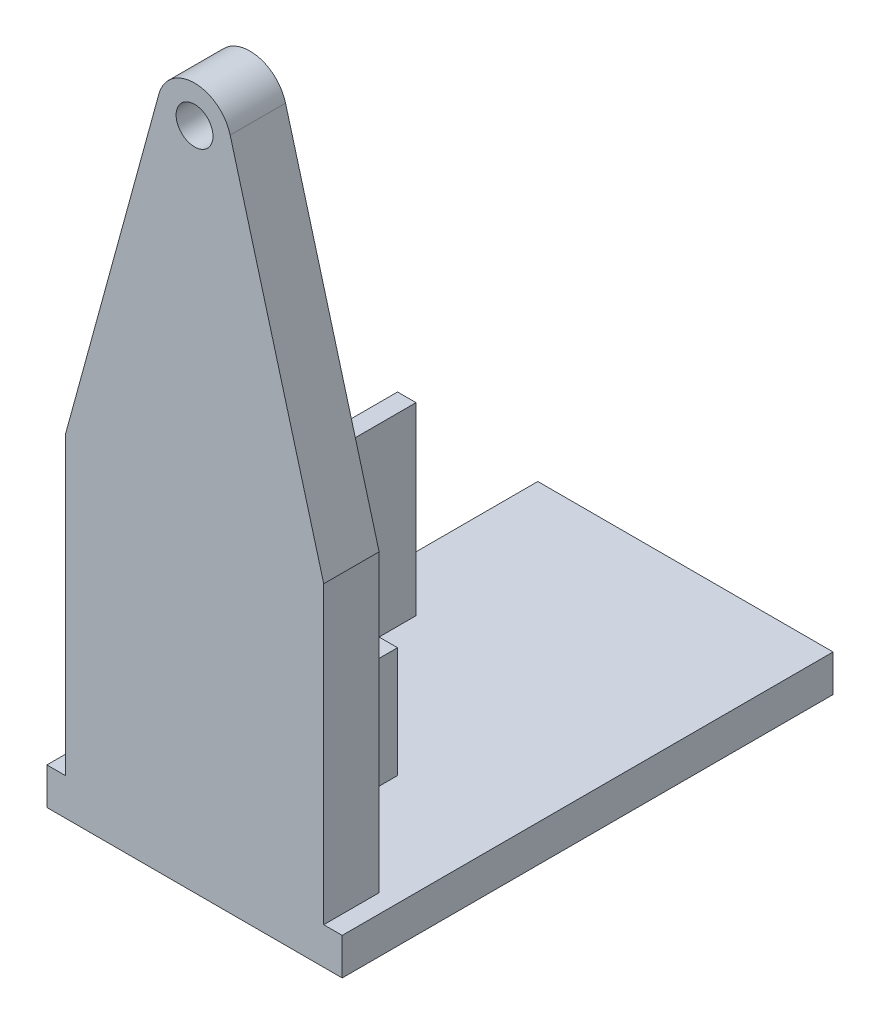
SolidWorks part; units mm, degrees
ref_plane "Front Plane" through (0, 0, 0) normal (0, 0, 1) x (1, 0, 0)
ref_plane "Top Plane" through (0, 0, 0) normal (0, 1, 0) x (1, 0, 0)
ref_plane "Right Plane" through (0, 0, 0) normal (1, 0, 0) x (0, 0, -1)
sketch "Sketch1" plane through (0, 0, 0) normal (0, 0, 1) x (1, 0, 0)
  line L0 (-40, 0) -> (40, 0)
  line L1 (40, 0) -> (40, 10)
  line L2 (40, 10) -> (-40, 10)
  line L3 (35, 10) -> (35, 90)
  line L4 (35, 90) -> (9.6562, 182.5997)
  line L5 (0, 0) -> (0, 190) construction
  line L6 (-35, 90) -> (-9.6453, 182.6398)
  line L7 (-35, 10) -> (-35, 90)
  line L8 (-40, 0) -> (-40, 10)
  circle A0 centre (0, 180) radius 10
  circle A1 centre (0, 180) radius 5
  point P4 (0, 180)
  point P12 (0, 10)
  dimension "D1" = 20
  dimension "D7" = 10
  dimension "D2" = 40
  dimension "D3" = 10
  dimension "D4" = 35
  dimension "D5" = 80
  dimension "D6" = 170
extrude "Boss-Extrude1" add sketch "Sketch1" along normal blind 15 contours L5 L0 L1 L2 | L2 L5 L6 L7 | L5 L2 L3 L4 | A0 | A1
sketch "Sketch2" plane through (0, 0, 0) normal (0, 0, -1) x (-1, 0, 0)
  line L1 (-40, 0) -> (40, 0)
  line L2 (-40, 0) -> (-40, 10)
  line L3 (-40, 10) -> (40, 10)
  line L4 (40, 0) -> (40, 10)
extrude "Boss-Extrude2" add sketch "Sketch2" along normal blind 118
sketch "Sketch3" plane through (0, 0, 0) normal (0, 0, -1) x (-1, 0, 0)
  line L0 (-10, 10) -> (10, 10)
  line L1 (35, 10) -> (-35, 10) construction
  line L2 (10, 10) -> (10, 40)
  line L3 (0, 180) -> (0, 10) construction
  line L4 (10, 40) -> (-10, 40)
  line L5 (-10, 10) -> (-10, 40)
  line L6 (-10, 100) -> (-15, 100)
  line L7 (10, 50) -> (15, 50)
  line L8 (10, 50) -> (10, 100)
  line L9 (10, 100) -> (15, 100)
  line L10 (15, 50) -> (15, 100)
  line L11 (-10, 50) -> (-10, 100)
  line L12 (-10, 50) -> (-15, 50)
  line L13 (-15, 50) -> (-15, 100)
  dimension "D1" = 10
  dimension "D2" = 30
  dimension "D3" = 5
  dimension "D4" = 50
  dimension "D5" = 10
  dimension "D6" = 10
extrude "Boss-Extrude3" add sketch "Sketch3" along normal blind 30
